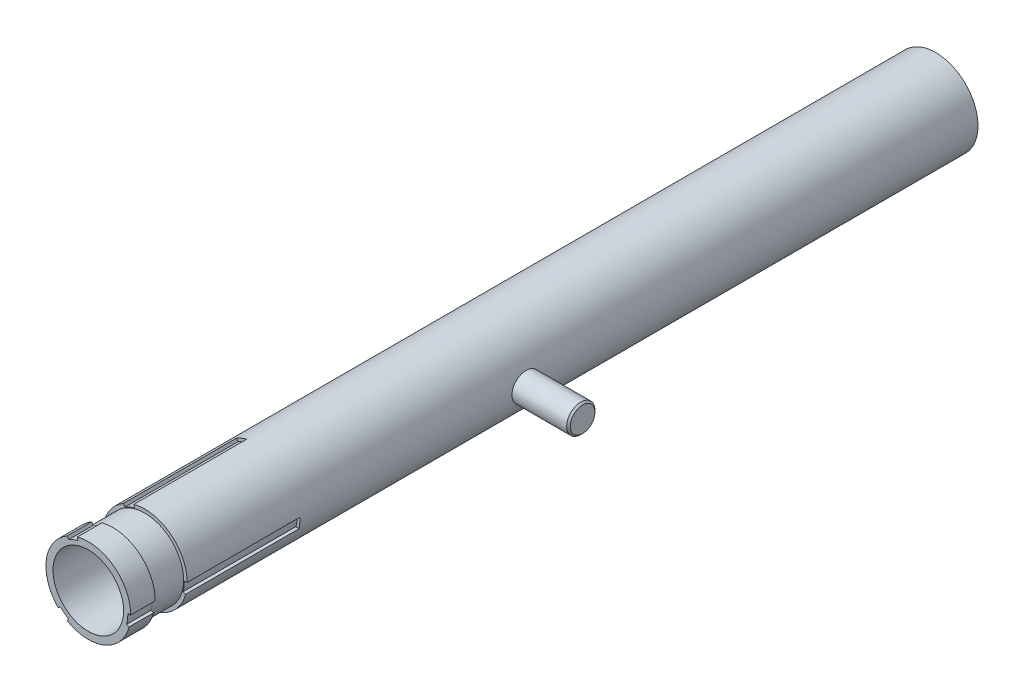
SolidWorks part; units mm, degrees
other "DetailItem1" parameters "RD1"=38.1
other "Weld Folder"
other "Weld Bead1"
material "2024 Alloy"
ref_plane "Front Plane" through (0, 0, 0) normal (0, 0, 1) x (1, 0, 0)
ref_plane "Top Plane" through (0, 0, 0) normal (0, 1, 0) x (1, 0, 0)
ref_plane "Right Plane" through (0, 0, 0) normal (1, 0, 0) x (0, 0, -1)
sketch "Sketch1" plane through (0, 0, 0) normal (0, 0, 1) x (1, 0, 0)
  circle A0 centre (0, 0) radius 15.875
  circle A1 centre (0, 0) radius 19.05
  dimension "D1" = 31.75
  dimension "D2" = 38.1
extrude "1968T51" add sketch "Sketch1" along normal blind 914.4
sketch "Sketch2" plane through (0, 0, 0) normal (0, 0, 1) x (1, 0, 0)
  circle A0 centre (0, 0) radius 19.05 construction
  circle A1 centre (0, 0) radius 19.05
extrude "Cut-Extrude1" cut sketch "Sketch2" along normal blind 76.2
ref_plane "Plane4" through (19.05, 0, 0) normal (1, 0, 0) x (0, 0, -1)
sketch "Sketch3" plane through (19.05, 0, 0) normal (1, 0, 0) x (0, 0, -1)
  line L2 (-76.2, -19.05) -> (-76.2, 19.05) construction
  circle A0 centre (-279.4, 0) radius 6.35
  dimension "D1" = 203.2
  dimension "D2" = 12.7
extrude "9061K36" add sketch "Sketch3" along normal blind 304.8 from offset 0
sketch "Sketch5" plane through (323.85, 0, 0) normal (1, 0, 0) x (0, 0, -1)
  circle A0 centre (-279.4, 0) radius 6.35 construction
  circle A1 centre (-279.4, 0) radius 6.35
extrude "Cut-Extrude3" cut sketch "Sketch5" against normal blind 279.4
chamfer "Chamfer1" distance 0.7937 angle 45 1 edges at (44.45, 0, 273.05)
sketch "Sketch6" plane through (0, 0, 914.4) normal (0, 0, 1) x (1, 0, 0)
  circle A0 centre (0, 0) radius 19.05 construction
  circle A1 centre (0, 0) radius 19.05
extrude "Cut-Extrude4" cut sketch "Sketch6" against normal blind 457.2
sketch "Sketch7" plane through (0, 0, 457.2) normal (0, 0, 1) x (1, 0, 0)
  line L0 (0, 19.05) -> (0, 17.78) construction
  line L1 (4.9305, 18.4009) -> (4.6018, 17.1742) construction
  line L2 (9.525, 16.4978) -> (8.89, 15.3979) construction
  line L3 (13.4704, 13.4704) -> (12.5724, 12.5724) construction
  line L4 (16.4978, 9.525) -> (15.3979, 8.89) construction
  line L5 (18.4009, 4.9305) -> (17.1742, 4.6018) construction
  line L6 (19.05, 0) -> (17.78, 0)
  line L7 (18.4009, -4.9305) -> (17.1742, -4.6018)
  line L8 (16.4978, -9.525) -> (15.3979, -8.89) construction
  line L9 (13.4704, -13.4704) -> (12.5724, -12.5724) construction
  line L10 (9.525, -16.4978) -> (8.89, -15.3979) construction
  line L11 (4.9305, -18.4009) -> (4.6018, -17.1742) construction
  line L12 (0, -19.05) -> (0, -17.78) construction
  line L13 (-4.9305, -18.4009) -> (-4.6018, -17.1742) construction
  line L14 (-9.525, -16.4978) -> (-8.89, -15.3979)
  line L15 (-13.4704, -13.4704) -> (-12.5724, -12.5724)
  line L16 (-16.4978, -9.525) -> (-15.3979, -8.89) construction
  line L17 (-18.4009, -4.9305) -> (-17.1742, -4.6018) construction
  line L18 (-19.05, 0) -> (-17.78, 0) construction
  line L19 (-18.4009, 4.9305) -> (-17.1742, 4.6018) construction
  line L20 (-16.4978, 9.525) -> (-15.3979, 8.89) construction
  line L21 (-13.4704, 13.4704) -> (-12.5724, 12.5724) construction
  line L22 (-9.525, 16.4978) -> (-8.89, 15.3979)
  line L23 (-4.9305, 18.4009) -> (-4.6018, 17.1742)
  arc A0 (-4.6018, 17.1742) -> (-8.89, 15.3979) centre (0, 0) ccw
  circle A1 centre (0, 0) radius 19.05
  arc A2 (-4.9305, 18.4009) -> (-9.525, 16.4978) centre (0, 0) ccw
  arc A3 (-12.5724, 12.5724) -> (-15.3979, 8.89) centre (0, 0) ccw construction
  arc A4 (-13.4704, 13.4704) -> (-16.4978, 9.525) centre (0, 0) ccw construction
  arc A5 (-17.1742, 4.6018) -> (-17.78, 0) centre (0, 0) ccw construction
  arc A6 (-18.4009, 4.9305) -> (-19.05, 0) centre (0, 0) ccw construction
  arc A7 (-18.4009, -4.9305) -> (-16.4978, -9.525) centre (0, 0) ccw construction
  arc A8 (-17.1742, -4.6018) -> (-15.3979, -8.89) centre (0, 0) ccw construction
  arc A9 (-12.5724, -12.5724) -> (-8.89, -15.3979) centre (0, 0) ccw
  arc A10 (-13.4704, -13.4704) -> (-9.525, -16.4978) centre (0, 0) ccw
  arc A11 (-4.9305, -18.4009) -> (0, -19.05) centre (0, 0) ccw construction
  arc A12 (-4.6018, -17.1742) -> (0, -17.78) centre (0, 0) ccw construction
  arc A13 (4.6018, -17.1742) -> (8.89, -15.3979) centre (0, 0) ccw construction
  arc A14 (4.9305, -18.4009) -> (9.525, -16.4978) centre (0, 0) ccw construction
  arc A15 (12.5724, -12.5724) -> (15.3979, -8.89) centre (0, 0) ccw construction
  arc A16 (13.4704, -13.4704) -> (16.4978, -9.525) centre (0, 0) ccw construction
  arc A17 (18.4009, -4.9305) -> (19.05, 0) centre (0, 0) ccw
  arc A18 (17.1742, -4.6018) -> (17.78, 0) centre (0, 0) ccw
  arc A19 (18.4009, 4.9305) -> (16.4978, 9.525) centre (0, 0) ccw construction
  arc A20 (17.1742, 4.6018) -> (15.3979, 8.89) centre (0, 0) ccw construction
  arc A21 (12.5724, 12.5724) -> (8.89, 15.3979) centre (0, 0) ccw construction
  arc A22 (13.4704, 13.4704) -> (9.525, 16.4978) centre (0, 0) ccw construction
  arc A23 (4.6018, 17.1742) -> (0, 17.78) centre (0, 0) ccw construction
  arc A24 (4.9305, 18.4009) -> (0, 19.05) centre (0, 0) ccw construction
  point P55 (0, 0)
  dimension "D2" = 35.56
  dimension "D3" = 24
  dimension "D1" = 0
extrude "Cut-Extrude5" cut sketch "Sketch7" against normal blind 76.2
sketch "Sketch8" plane through (0, 0, 457.2) normal (0, 0, 1) x (1, 0, 0)
  arc A0 (1.265, 17.4166) -> (-5.4696, -16.5838) centre (0, 0) ccw construction
  arc A1 (1.265, 17.4166) -> (-5.4696, -16.5838) centre (0, 0) ccw construction
  circle A2 centre (0, 0) radius 17.4625
  circle A4 centre (0, 0) radius 19.05
extrude "Cut-Extrude6" cut sketch "Sketch8" along normal blind 14.351 from surface
equation "\"Main Tube Cut length\"= 3in"
equation "\"Nub tube cut length\"= 11in"
equation "\"D1@Cut-Extrude1\"=\"Main Tube Cut length\""
equation "\"D1@Cut-Extrude3\"=\"Nub tube cut length\""
